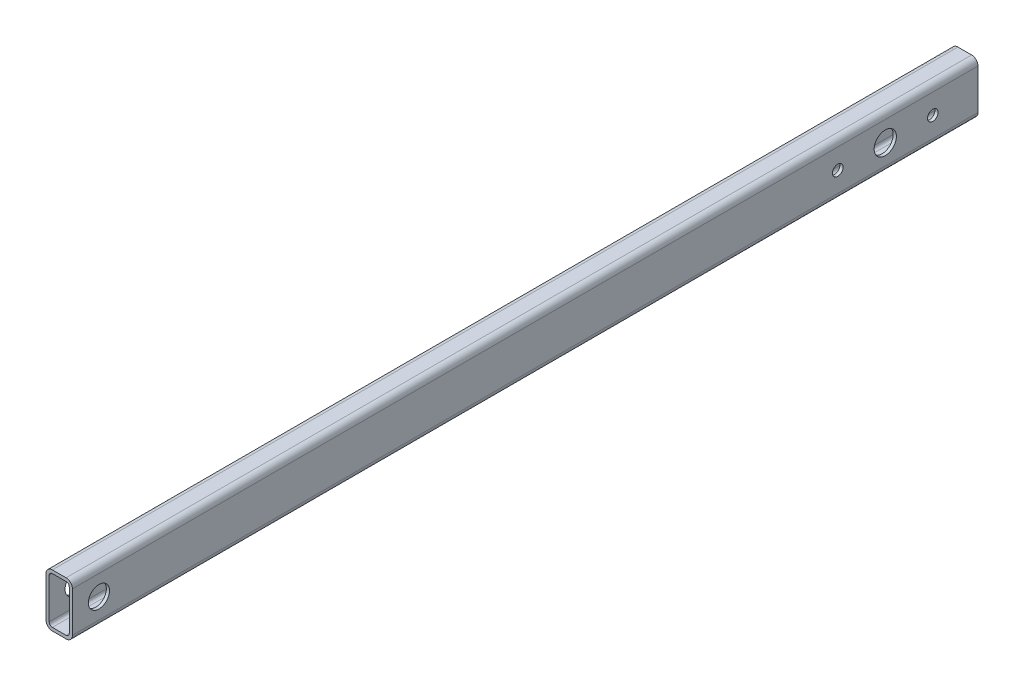
SolidWorks part; units mm, degrees
material "AISI 1020 Steel, Cold Rolled"
ref_plane "Front Plane" through (0, 0, 0) normal (0, 0, 1) x (1, 0, 0)
ref_plane "Top Plane" through (0, 0, 0) normal (0, 1, 0) x (1, 0, 0)
ref_plane "Right Plane" through (0, 0, 0) normal (1, 0, 0) x (0, 0, -1)
sketch "Sketch1" plane through (0, 0, 0) normal (0, 0, 1) x (1, 0, 0)
  line L4 (0, 44) -> (0, 6)
  line L10 (3, 44) -> (3, 6)
  line L11 (6, 47) -> (18.9612, 47)
  line L12 (21.9612, 44) -> (21.9612, 6)
  line L13 (24.9612, 44) -> (24.9612, 6)
  line L14 (6, 50) -> (18.9612, 50)
  line L15 (6, 3) -> (18.9612, 3)
  line L16 (6, 0) -> (18.9612, 0)
  arc A0 (6, 3) -> (3, 6) centre (6, 6) cw
  arc A1 (6, 0) -> (0, 6) centre (6, 6) cw
  arc A2 (18.9612, 3) -> (21.9612, 6) centre (18.9612, 6) ccw
  arc A3 (18.9612, 0) -> (24.9612, 6) centre (18.9612, 6) ccw
  arc A4 (6, 47) -> (3, 44) centre (6, 44) ccw
  arc A5 (6, 50) -> (0, 44) centre (6, 44) ccw
  arc A6 (18.9612, 47) -> (21.9612, 44) centre (18.9612, 44) cw
  arc A7 (18.9612, 50) -> (24.9612, 44) centre (18.9612, 44) cw
sketch "Sketch2" plane through (0, 0, 0) normal (0, 0, 1) x (1, 0, 0)
  line L4 (0, 44) -> (0, 6)
  line L10 (3, 44) -> (3, 6)
  line L11 (6, 47) -> (18.9612, 47)
  line L12 (21.9612, 44) -> (21.9612, 6)
  line L13 (24.9612, 44) -> (24.9612, 6)
  line L14 (6, 50) -> (18.9612, 50)
  line L15 (6, 3) -> (18.9612, 3)
  line L16 (6, 0) -> (18.9612, 0)
  arc A0 (6, 3) -> (3, 6) centre (6, 6) cw
  arc A1 (6, 0) -> (0, 6) centre (6, 6) cw
  arc A2 (18.9612, 3) -> (21.9612, 6) centre (18.9612, 6) ccw
  arc A3 (18.9612, 0) -> (24.9612, 6) centre (18.9612, 6) ccw
  arc A4 (6, 47) -> (3, 44) centre (6, 44) ccw
  arc A5 (6, 50) -> (0, 44) centre (6, 44) ccw
  arc A6 (18.9612, 47) -> (21.9612, 44) centre (18.9612, 44) cw
  arc A7 (18.9612, 50) -> (24.9612, 44) centre (18.9612, 44) cw
extrude "Boss-Extrude1" add sketch "Sketch1" along normal blind 785 and the other way blind 70
sketch "Sketch3" plane through (24.9612, 0, 0) normal (1, 0, 0) x (0, 0, -1)
  line L0 (-785, 25) -> (-760, 25)
  line L1 (-760, 25) -> (-655, 25)
  line L2 (-785, 6) -> (-785, 44) construction
  line L3 (-655, 25) -> (-380, 25)
  circle A1 centre (-17.5503, 25) radius 10.5
  circle A2 centre (27.2997, 25) radius 5
  circle A3 centre (-62.4003, 25) radius 5
  circle A4 centre (-760, 25) radius 10
  circle A6 centre (-380, 25) radius 10
extrude "Cut-Extrude1" cut sketch "Sketch3" against normal through all contours A1 | A3 | L1 A4 L0 | L0 A4 L1 | A2
